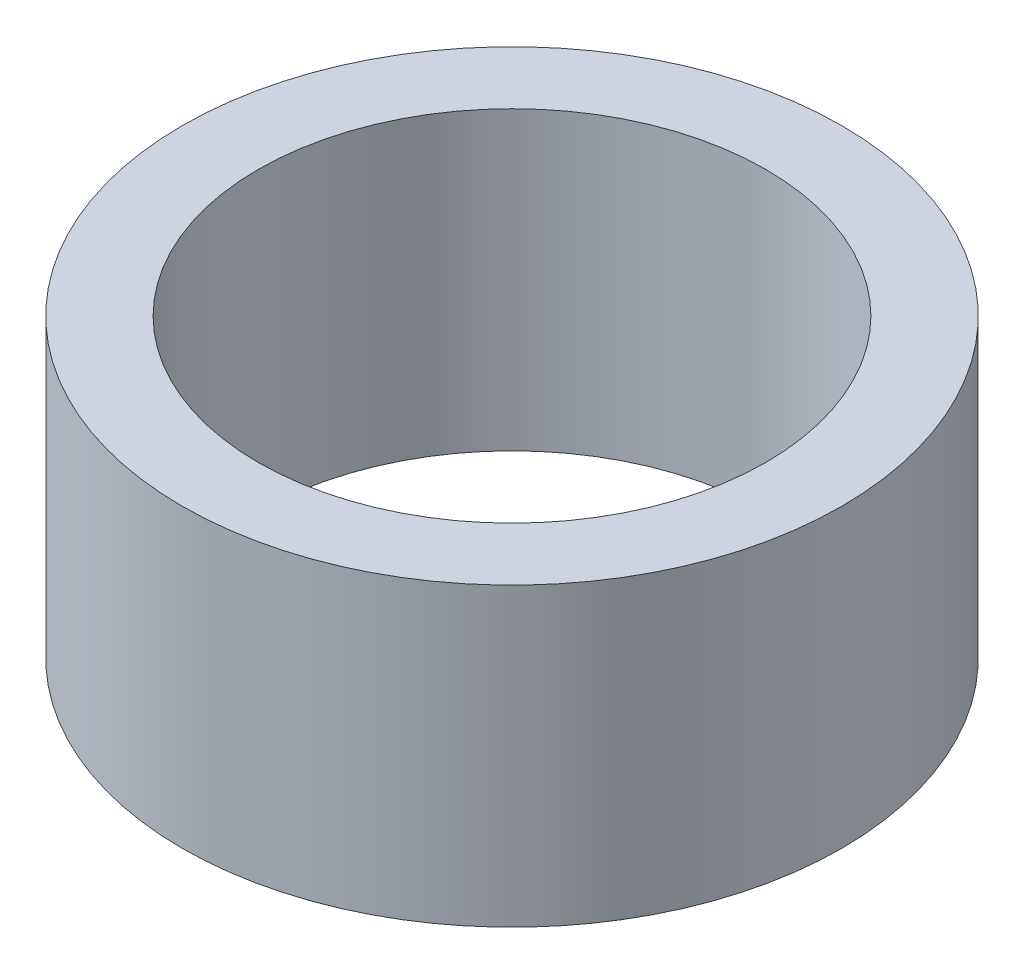
SolidWorks part; units mm, degrees
ref_plane "Front Plane" through (0, 0, 0) normal (0, 0, 1) x (1, 0, 0)
ref_plane "Top Plane" through (0, 0, 0) normal (0, 1, 0) x (1, 0, 0)
ref_plane "Right Plane" through (0, 0, 0) normal (1, 0, 0) x (0, 0, -1)
sketch "Sketch1" plane through (0, 0, 0) normal (0, 1, 0) x (1, 0, 0)
  line L1 (7.3323, 0) -> (3.6662, 6.35)
  line L2 (3.6662, 6.35) -> (-3.6662, 6.35)
  line L3 (-3.6662, 6.35) -> (-7.3323, 0)
  line L4 (-7.3323, 0) -> (-3.6662, -6.35)
  line L5 (-3.6662, -6.35) -> (3.6662, -6.35)
  line L6 (3.6662, -6.35) -> (7.3323, 0)
  circle A0 centre (0, 0) radius 9.525
  circle A1 centre (0, 0) radius 6.35 construction
  circle A2 centre (0, 0) radius 7.3323
  dimension "D1" = 12.7
  dimension "D2" = 19.05
extrude "Boss-Extrude1" add sketch "Sketch1" along normal blind 8.5598 contours A0 A2
